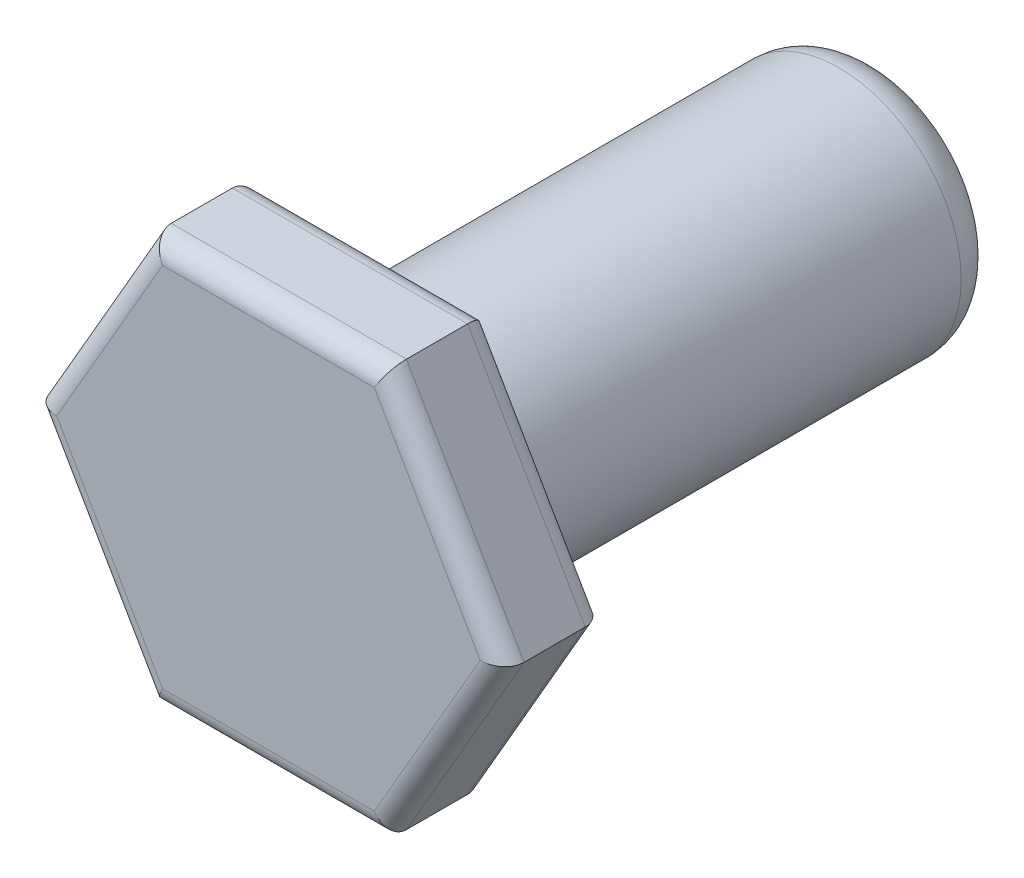
SolidWorks part; units mm, degrees
ref_plane "前视基准面" through (0, 0, 0) normal (0, 0, 1) x (1, 0, 0)
ref_plane "上视基准面" through (0, 0, 0) normal (0, 1, 0) x (1, 0, 0)
ref_plane "右视基准面" through (0, 0, 0) normal (1, 0, 0) x (0, 0, -1)
sketch "草图1" plane through (0, 0, 0) normal (0, 0, 1) x (1, 0, 0)
  circle A0 centre (0, 0) radius 6
  dimension "D1" = 12
extrude "凸台-拉伸1" add sketch "草图1" along normal blind 25
sketch "草图2" plane through (0, 0, 25) normal (0, 0, 1) x (1, 0, 0)
  line L1 (5.7735, -10) -> (11.547, 0)
  line L2 (11.547, 0) -> (5.7735, 10)
  line L3 (5.7735, 10) -> (-5.7735, 10)
  line L4 (-5.7735, 10) -> (-11.547, 0)
  line L5 (-11.547, 0) -> (-5.7735, -10)
  line L6 (-5.7735, -10) -> (5.7735, -10)
  circle A0 centre (0, 0) radius 10 construction
  dimension "D1" = 20
extrude "凸台-拉伸2" add sketch "草图2" along normal blind 5
fillet "圆角1" radius 2 1 edges at (6, 0, 0)
fillet "圆角2" radius 1 12 edges at (8.6603, 5, 25) (8.6603, -5, 25) (0, -10, 30) (0, -10, 25) (0, 10, 25) (-8.6603, 5, 25) (-8.6603, 5, 30) (-8.6603, -5, 30) (-8.6603, -5, 25) (8.6603, -5, 30) (8.6603, 5, 30) (0, 10, 30)
